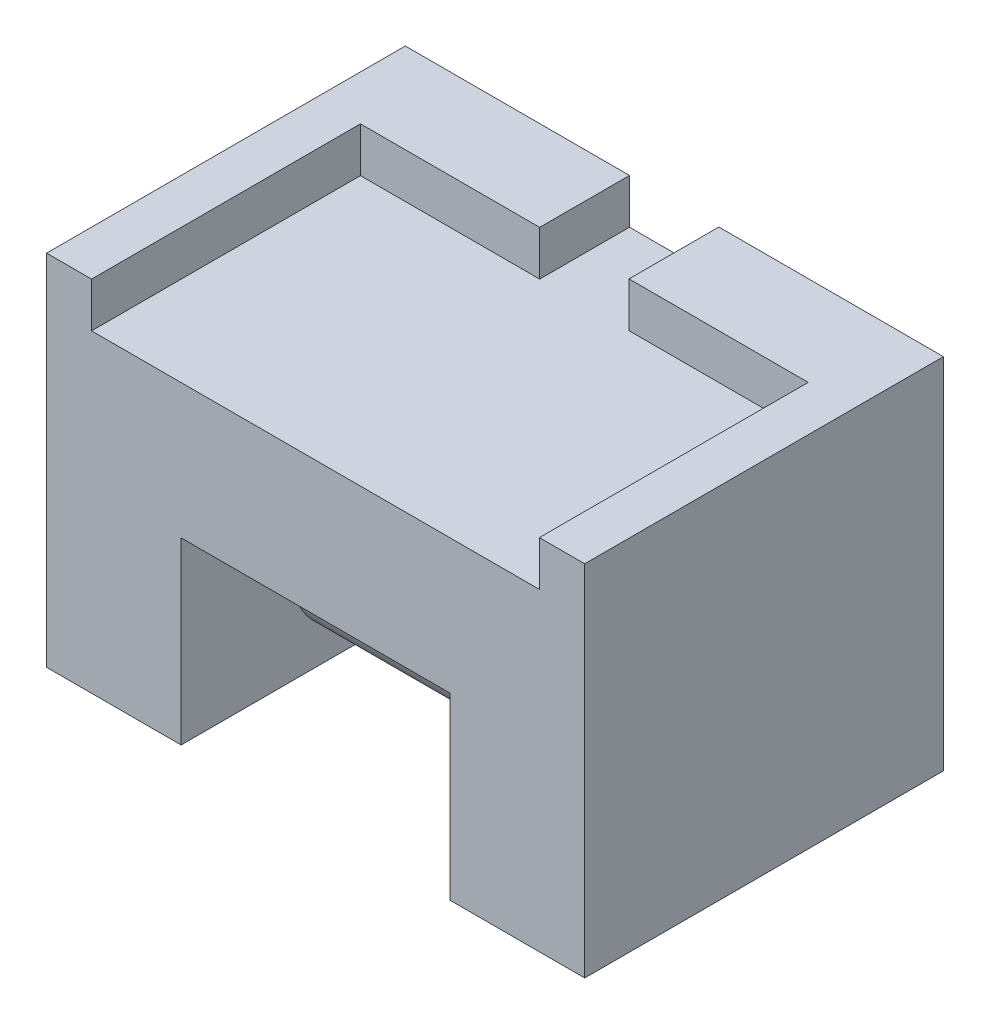
SolidWorks part; units mm, degrees
material "ASTM A36 Steel"
ref_plane "Front Plane" through (0, 0, 0) normal (0, 0, 1) x (1, 0, 0)
ref_plane "Top Plane" through (0, 0, 0) normal (0, 1, 0) x (1, 0, 0)
ref_plane "Right Plane" through (0, 0, 0) normal (1, 0, 0) x (0, 0, -1)
sketch "Sketch2" plane through (0, 0, 0) normal (0, 0, 1) x (1, 0, 0)
  line L1 (-7.9809, 8.5014) -> (68.2191, 8.5014)
  line L2 (-7.9809, 8.5014) -> (-7.9809, -16.8986)
  line L3 (-7.9809, -16.8986) -> (68.2191, -16.8986)
  line L4 (68.2191, 8.5014) -> (68.2191, -16.8986)
  dimension "D1" = 25.4
  dimension "D2" = 76.2
extrude "Boss-Extrude1" add sketch "Sketch2" along normal blind 50.8
sketch "Sketch3" plane through (0, -16.8986, 0) normal (0, -1, 0) x (1, 0, 0)
  line L0 (-7.9809, 0) -> (68.2191, 0) construction
  line L1 (-7.9809, 50.8) -> (11.0691, 50.8)
  line L2 (-7.9809, 50.8) -> (-7.9809, 0)
  line L3 (-7.9809, 0) -> (11.0691, 0)
  line L4 (11.0691, 50.8) -> (11.0691, 0)
  line L6 (68.2191, 50.8) -> (49.1691, 50.8)
  line L7 (68.2191, 50.8) -> (68.2191, 0)
  line L8 (68.2191, 0) -> (49.1691, 0)
  line L9 (49.1691, 50.8) -> (49.1691, 0)
  dimension "D1" = 19.05
  dimension "D2" = 19.05
extrude "Boss-Extrude2" add sketch "Sketch3" along normal blind 25.4
sketch "Sketch4" plane through (11.0691, 0, 0) normal (1, 0, 0) x (0, 0, -1)
  line L0 (-50.8, -42.2986) -> (-50.8, 8.5014) construction
  line L2 (0, -42.2986) -> (-50.8, -42.2986) construction
  circle A0 centre (-25.4, -29.5986) radius 9.525
  dimension "D1" = 19.05
  dimension "D2" = 25.4
  dimension "D3" = 12.7
extrude "Boss-Extrude3" add sketch "Sketch4" along normal blind 50.8
sketch "Sketch7" plane through (0, 8.5014, 0) normal (0, 1, 0) x (1, 0, 0)
  line L0 (68.2191, -50.8) -> (-7.9809, -50.8) construction
  line L1 (-1.6106, -50.8) -> (61.798, -50.8)
  line L2 (-1.6106, -50.8) -> (-1.6106, -12.7254)
  line L3 (-1.6106, -12.7254) -> (61.798, -12.7254)
  line L4 (61.798, -50.8) -> (61.798, -12.7254)
  line L5 (68.2191, 0) -> (-7.9809, 0) construction
  line L6 (23.7691, -12.7254) -> (36.4183, -12.7254)
  line L7 (23.7691, -12.7254) -> (23.7691, 0)
  line L8 (23.7691, 0) -> (36.4183, 0)
  line L9 (36.4183, -12.7254) -> (36.4183, 0)
  line L10 (-7.9809, -50.8) -> (-7.9809, 0) construction
  line L11 (68.2191, -50.8) -> (68.2191, 0) construction
  line M9 (68.2191, 0) -> (-7.9809, 0)
  line M11 (-7.9809, -50.8) -> (68.2191, -50.8)
  dimension "D1" = 38.0746
  dimension "D2" = 12.6492
  dimension "D3" = 31.75
  dimension "D4" = 31.8008
  dimension "D5" = 25.3797
  dimension "D6" = 25.3797
extrude "Cut-Extrude1" cut sketch "Sketch7" against normal blind 6.35 contours L4 L3 L2 M11 | L3 L9 L7 M9
